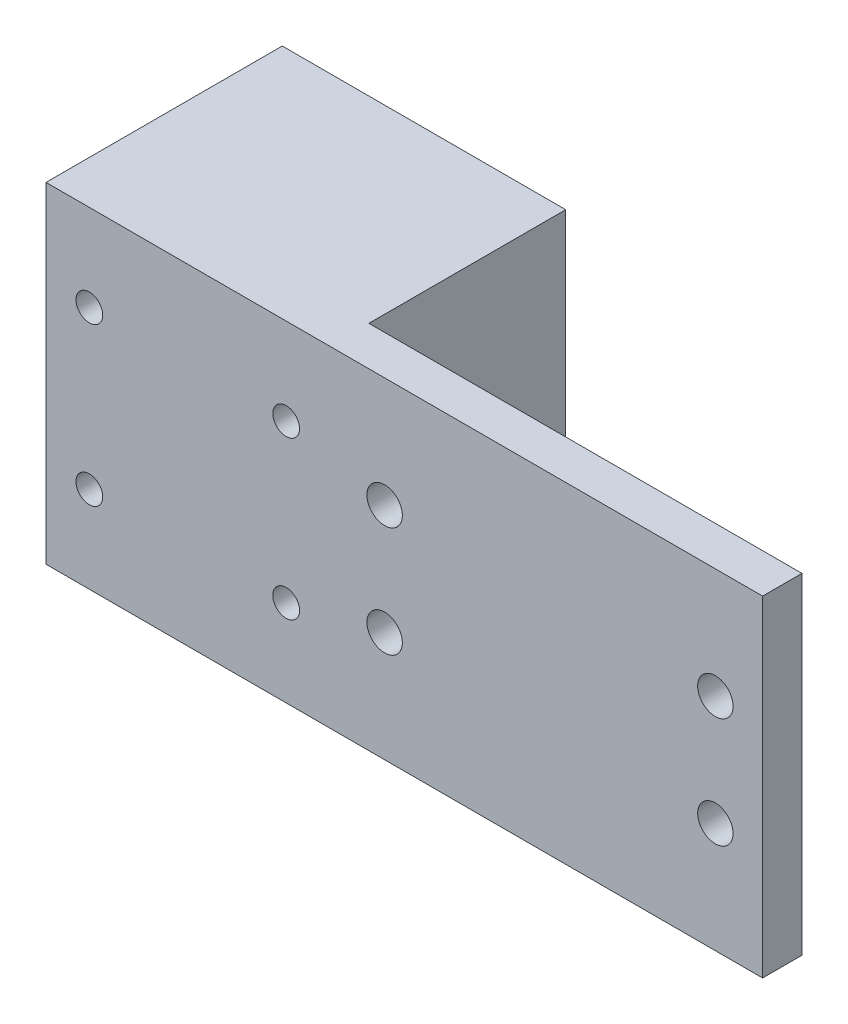
SolidWorks part; units mm, degrees
ref_plane "정면" through (0, 0, 0) normal (0, 0, 1) x (1, 0, 0)
ref_plane "윗면" through (0, 0, 0) normal (0, 1, 0) x (1, 0, 0)
ref_plane "우측면" through (0, 0, 0) normal (1, 0, 0) x (0, 0, -1)
sketch "스케치1" plane through (0, 0, 0) normal (0, 1, 0) x (1, 0, 0)
  line L0 (0, 0) -> (0, 30)
  line L1 (0, 30) -> (36, 30)
  line L2 (36, 30) -> (36, 5)
  line L3 (36, 5) -> (91, 5)
  line L4 (91, 5) -> (91, 0)
  line L5 (91, 0) -> (0, 0)
  dimension "D1" = 36
  dimension "D2" = 55
  dimension "D3" = 25
  dimension "D4" = 5
extrude "보스-돌출1" add sketch "스케치1" along normal blind 42
hole_wizard "M4 여유 구멍1" positions "스케치3" profile "스케치2" hole size "M4" standard "Ansi Metric" end condition through all
sketch "스케치3" plane through (0, 0, 0) normal (0, 0, 1) x (1, 0, 0)
  line L0 (85, 28) -> (85, 42) construction
  line L1 (0, 42) -> (91, 42) construction
  line L7 (85, 14) -> (85, 28) construction
  line L10 (85, 14) -> (85, 0) construction
  line L11 (0, 0) -> (91, 0) construction
  line L13 (91, 42) -> (91, 0) construction
  line L14 (85, 28) -> (43, 28) construction
  line L15 (43, 28) -> (43, 14) construction
  line L16 (43, 14) -> (85, 14) construction
  point P0 (85, 28)
  point P6 (85, 14)
  point P40 (43, 28)
  point P42 (43, 14)
  dimension "D1" = 6
  dimension "D2" = 14
  dimension "D3" = 42
sketch "스케치2" plane through (85, 28, 0) normal (1, 0, 0) x (0, -1, 0)
  line L0 (0, 0) -> (0, 30)
  line L1 (0, 30) -> (2.25, 30)
  line L2 (2.25, 30) -> (2.25, 0)
  line L5 (2.25, 0) -> (0, 0)
  line L11 (0, -6.35) -> (0, 107.95) construction
  dimension "관통 구멍 지름" = 4.5
  dimension "관통 구멍 깊이" = 30
hole_wizard "M3 여유 구멍1" positions "스케치5" profile "스케치4" hole size "M3" standard "Ansi Metric" end condition through all
sketch "스케치5" plane through (0, 0, 0) normal (0, 0, 1) x (1, 0, 0)
  line L2 (5.5, 31) -> (5.5, 11)
  line L5 (5.5, 31) -> (5.5, 42) construction
  line L6 (0, 42) -> (91, 42) construction
  line L9 (5.5, 11) -> (5.5, 0) construction
  line L10 (0, 0) -> (91, 0) construction
  line L14 (0, 42) -> (0, 0) construction
  line L15 (5.5, 31) -> (30.5, 31) construction
  line L16 (30.5, 31) -> (30.5, 11) construction
  line L17 (30.5, 11) -> (5.5, 11) construction
  point P1 (5.5, 31)
  point P67 (5.5, 11)
  point P101 (30.5, 31)
  point P103 (30.5, 11)
  dimension "D1" = 20
  dimension "D2" = 25
  dimension "D3" = 5.5
sketch "스케치4" plane through (5.5, 31, 0) normal (1, 0, 0) x (0, -1, 0)
  line L0 (0, 0) -> (0, 30)
  line L1 (0, 30) -> (1.7, 30)
  line L2 (1.7, 30) -> (1.7, 0)
  line L5 (1.7, 0) -> (0, 0)
  line L11 (0, -6.35) -> (0, 107.95) construction
  dimension "관통 구멍 지름" = 3.4
  dimension "관통 구멍 깊이" = 30
hole_wizard "M4x0.7 나사 구멍1" [suppressed] positions "스케치16" profile "스케치15" tap size "M4x0.7" standard "Ansi Metric"
sketch "스케치16" plane through (0, 0, 0) normal (0, 0, 1) x (1, 0, 0)
  line L0 (91, 21) -> (78, 21) construction
  line L1 (91, 42) -> (91, 0) construction
  line L2 (78, 21) -> (13, 21) construction
  line L3 (13, 21) -> (0, 21) construction
  line L4 (0, 42) -> (0, 0) construction
  point P2 (78, 21)
  point P6 (13, 21)
  dimension "D1" = 65
sketch "스케치15" plane through (78, 21, 0) normal (1, 0, 0) x (0, -1, 0)
  line L0 (0, 0) -> (0, 12.4914)
  line L1 (0, 12.4914) -> (1.65, 11.5)
  line L2 (1.65, 11.5) -> (1.65, 0)
  line L5 (1.65, 0) -> (0, 0)
  line L10 (0, 12.4914) -> (-1.65, 11.5) construction
  line L11 (0, -6.35) -> (0, 107.95) construction
  dimension "탭 드릴 지름" = 3.3
  dimension "탭 드릴 깊이" = 11.5
  dimension "드릴 각도" = 118
cosmetic thread "구멍 나사산1" [suppressed] parameters "D1"=8, "D2"=4
cosmetic thread "구멍 나사산2" [suppressed] parameters "D1"=8, "D2"=4
